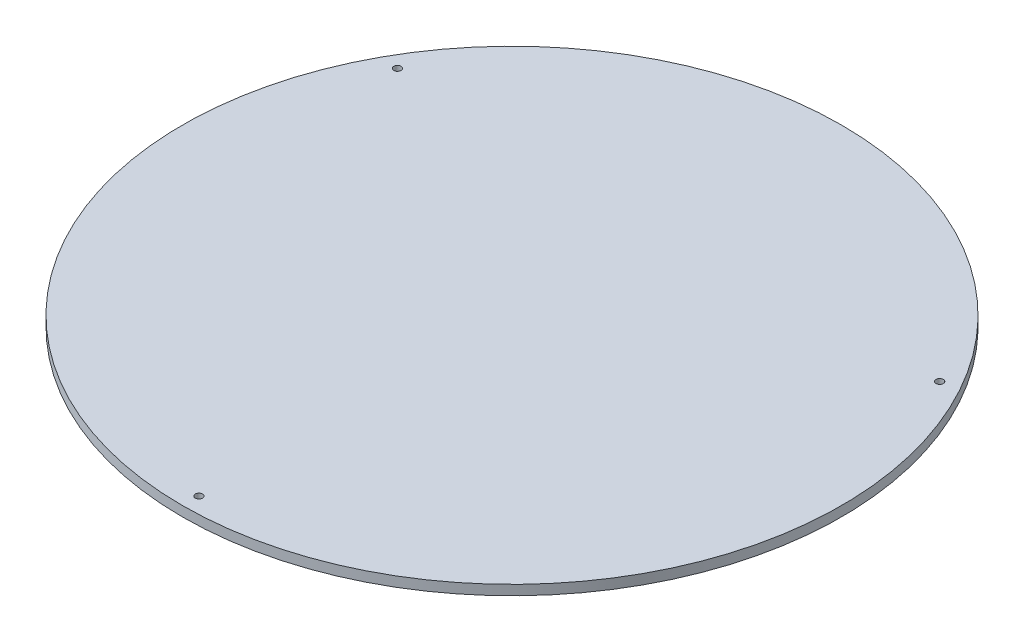
SolidWorks part; units mm, degrees
ref_plane "前视基准面" through (0, 0, 0) normal (0, 0, 1) x (1, 0, 0)
ref_plane "上视基准面" through (0, 0, 0) normal (0, 1, 0) x (1, 0, 0)
ref_plane "右视基准面" through (0, 0, 0) normal (1, 0, 0) x (0, 0, -1)
other "Configuration Table"
sketch "草图1" plane through (0, 0, 0) normal (0, 1, 0) x (1, 0, 0)
  circle A0 centre (0, 0) radius 100
  dimension "D1" = 200
extrude "凸台-拉伸1" add sketch "草图1" along normal blind 3
sketch "草图2" plane through (0, 3, 0) normal (0, 1, 0) x (1, 0, 0)
  circle A0 centre (0, -95) radius 1.1
  circle A1 centre (-82.2724, 47.5) radius 1.1
  circle A2 centre (82.2724, 47.5) radius 1.1
  point P10 (0, 0)
  dimension "D2" = 2.2
  dimension "D1" = 95
  dimension "D3" = 3
extrude "切除-拉伸1" cut sketch "草图2" against normal up to next
